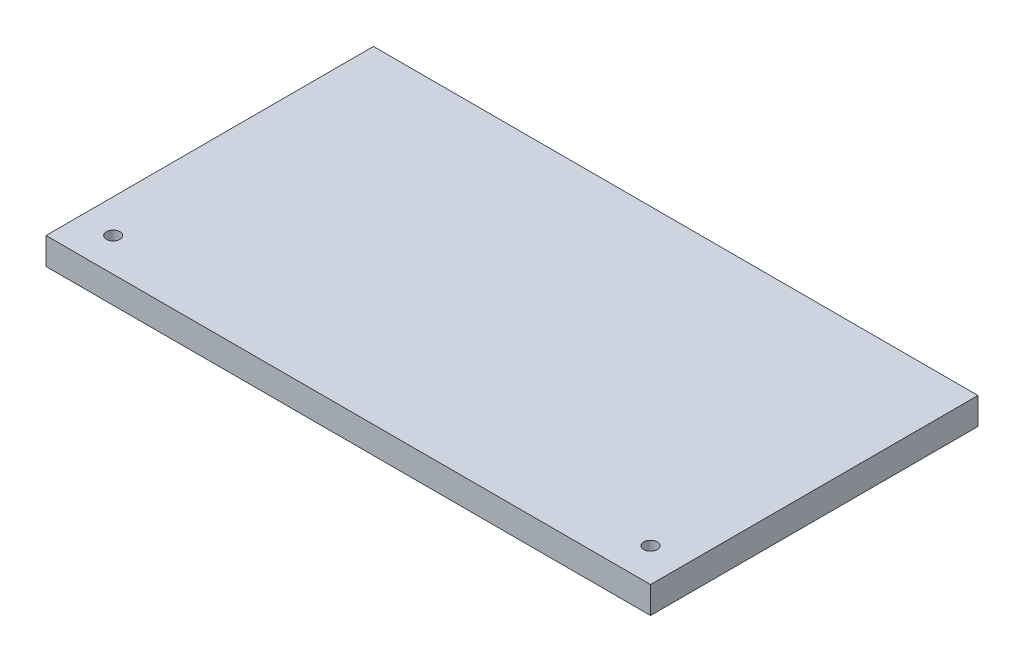
SolidWorks part; units mm, degrees
material "Сосна"
ref_plane "Front Plane" through (0, 0, 0) normal (0, 0, 1) x (1, 0, 0)
ref_plane "Top Plane" through (0, 0, 0) normal (0, 1, 0) x (1, 0, 0)
ref_plane "Right Plane" through (0, 0, 0) normal (1, 0, 0) x (0, 0, -1)
sketch "Эскиз1" plane through (0, 0, 0) normal (0, 1, 0) x (1, 0, 0)
  line L1 (-360, 195) -> (0, 195)
  line L2 (-360, 195) -> (-360, 0)
  line L3 (-360, 0) -> (0, 0)
  line L4 (0, 195) -> (0, 0)
  circle A0 centre (-340, 20) radius 4
  circle A1 centre (-20, 20) radius 4
  dimension "D3" = 8
  dimension "D5" = 20
  dimension "D6" = 320
  dimension "D1" = 360
  dimension "D2" = 195
  dimension "D4" = 20
  dimension "D7" = 20
extrude "Бобышка-Вытянуть1" add sketch "Эскиз1" along normal blind 16
